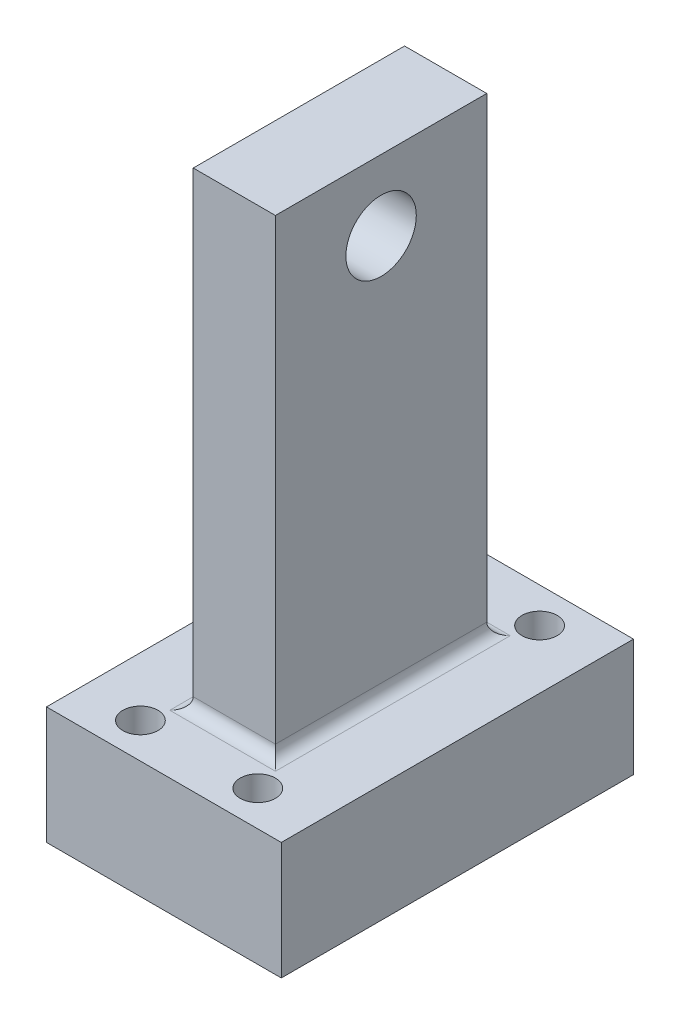
SolidWorks part; units mm, degrees
ref_plane "Front Plane" through (0, 0, 0) normal (0, 0, 1) x (1, 0, 0)
ref_plane "Top Plane" through (0, 0, 0) normal (0, 1, 0) x (1, 0, 0)
ref_plane "Right Plane" through (0, 0, 0) normal (1, 0, 0) x (0, 0, -1)
sketch "Sketch1" plane through (0, 0, 0) normal (0, 1, 0) x (1, 0, 0)
  line L0 (10, 30) -> (10, 0) construction
  line L1 (0, 0) -> (20, 0)
  line L2 (0, 0) -> (0, 30)
  line L3 (0, 30) -> (20, 30)
  line L4 (20, 0) -> (20, 30)
  line L6 (0, 27) -> (20, 27) construction
  line L15 (0, 0) -> (10, 0)
  line L25 (0, 3) -> (20, 3) construction
  circle A4 centre (5, 27) radius 1.5
  circle A5 centre (15, 27) radius 1.5
  circle A6 centre (5, 3) radius 1.5
  circle A7 centre (15, 3) radius 1.5
  dimension "D5" = 3
  dimension "D1" = 20
  dimension "D2" = 30
  dimension "D3" = 5
  dimension "D4" = 5
  dimension "D12" = 3
  dimension "D14" = 3
extrude "Boss-Extrude1" add sketch "Sketch1" along normal blind 10
sketch "Sketch2" plane through (0, 10, 0) normal (0, 1, 0) x (1, 0, 0)
  line L17 (10, 30) -> (10, 0) construction
  line L18 (0, 30) -> (20, 30) construction
  line L19 (0, 0) -> (20, 0) construction
  line L20 (0, 15) -> (20, 15) construction
  line L21 (0, 0) -> (0, 30) construction
  line L22 (20, 0) -> (20, 30) construction
  line L24 (6.5, 6) -> (13.5, 6)
  line L25 (6.5, 6) -> (6.5, 24)
  line L26 (6.5, 24) -> (13.5, 24)
  line L27 (13.5, 6) -> (13.5, 24)
  line L28 (6.5, 6) -> (13.5, 24) construction
  line L29 (6.5, 24) -> (13.5, 6) construction
  point P12 (10, 15)
  dimension "D1" = 18
  dimension "D2" = 7
extrude "Boss-Extrude2" add sketch "Sketch2" along normal blind 40
sketch "Sketch3" plane through (13.5, 0, 0) normal (1, 0, 0) x (0, 0, -1)
  line L0 (15, 50) -> (15, 10) construction
  line L1 (6, 50) -> (24, 50) construction
  line L2 (6, 10) -> (24, 10) construction
  line L3 (6, 44) -> (24, 44) construction
  line L4 (6, 50) -> (6, 10) construction
  line L5 (24, 50) -> (24, 10) construction
  circle A0 centre (15, 44) radius 3
  dimension "D2" = 6
  dimension "D1" = 6
extrude "Cut-Extrude1" cut sketch "Sketch3" against normal blind 40
fillet "Fillet1" radius 1 4 edges at (10, 10, -24) (6.5, 10, -15) (13.5, 10, -15) (10, 10, -6)
